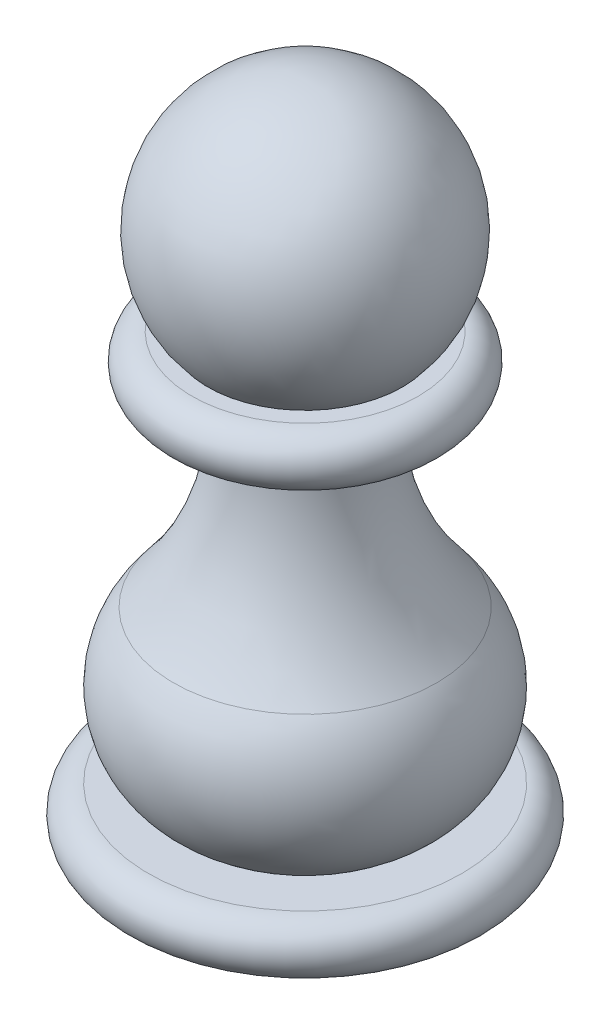
SolidWorks part; units mm, degrees
ref_plane "Front Plane" through (0, 0, 0) normal (0, 0, 1) x (1, 0, 0)
ref_plane "Top Plane" through (0, 0, 0) normal (0, 1, 0) x (1, 0, 0)
ref_plane "Right Plane" through (0, 0, 0) normal (1, 0, 0) x (0, 0, -1)
sketch "Sketch1" plane through (0, 0, 0) normal (0, 0, 1) x (1, 0, 0)
  line L0 (4, -15.5) -> (6.5, -15.5)
  line L3 (0, 0) -> (0, 6.1566) construction
  line L4 (5.5902, -12.5) -> (6.5, -12.5)
  line L7 (9, -36.5) -> (9, -24.844) construction
  line L8 (6.5, -35) -> (9, -35)
  line L9 (0, -38) -> (9, -38)
  line L10 (0, 0) -> (0, -38)
  arc A0 (0, 0) -> (5.5902, -12.5) centre (0, -7.5) cw
  arc A3 (4, -15.5) -> (7.5621, -26.2296) centre (18.9675, -16.487) ccw
  arc A4 (7.5621, -26.2296) -> (6.5, -35) centre (3, -30.1266) cw
  arc A7 (6.5, -12.5) -> (6.5, -15.5) centre (6.5, -14) cw
  arc A8 (9, -35) -> (9, -38) centre (9, -36.5) cw
  point P3 (6.5, -35)
  point P6 (0, 0)
  dimension "D1" = 7.5
  dimension "D3" = 6.5
  dimension "D5" = 15
  dimension "D6" = 6
  dimension "D9" = 1.5
  dimension "D12" = 9
  dimension "D2" = 1.5
  dimension "D4" = 3
  dimension "D7" = 6.5
  dimension "D8" = 3
  dimension "D10" = 4
  dimension "D11" = 12.5
  dimension "D13" = 38
revolve "Revolve5" add sketch "Sketch1" angle 360 about L3
